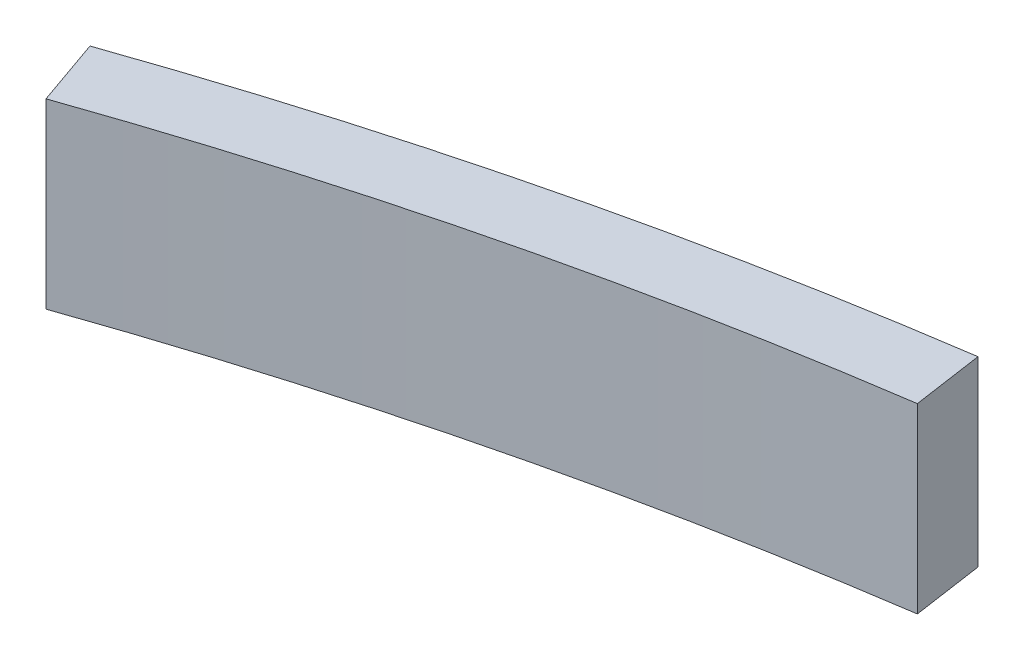
SolidWorks part; units mm, degrees
ref_plane "Front Plane" through (0, 0, 0) normal (0, 0, 1) x (1, 0, 0)
ref_plane "Top Plane" through (0, 0, 0) normal (0, 1, 0) x (1, 0, 0)
ref_plane "Right Plane" through (0, 0, 0) normal (1, 0, 0) x (0, 0, -1)
sketch "Sketch1" plane through (0, 0, 0) normal (0, 1, 0) x (1, 0, 0)
  line L0 (-173.0911, 494.5862) -> (0, 0) construction
  line L1 (0, 0) -> (-75.5394, 518.5266) construction
  line L2 (-173.0911, 494.5862) -> (-176.3943, 504.0248)
  line L3 (-75.5394, 518.5266) -> (-76.981, 528.4221)
  arc A0 (-173.0911, 494.5862) -> (-75.5394, 518.5266) centre (0, 0) cw
  arc A1 (-176.3943, 504.0248) -> (-76.981, 528.4221) centre (0, 0) cw
  dimension "D1" = 524
  dimension "D2" = 11
extrude "Boss-Extrude1" add sketch "Sketch1" along normal blind 25.4
sketch "Sketch2" plane through (0, 0, 0) normal (0, 1, 0) x (1, 0, 0)
  line L0 (-76.981, 528.4221) -> (-92.1296, 541.7242)
  line L1 (-92.1296, 541.7242) -> (-168.5905, 525.5422)
  line L2 (-168.5905, 525.5422) -> (-176.3943, 504.0248)
